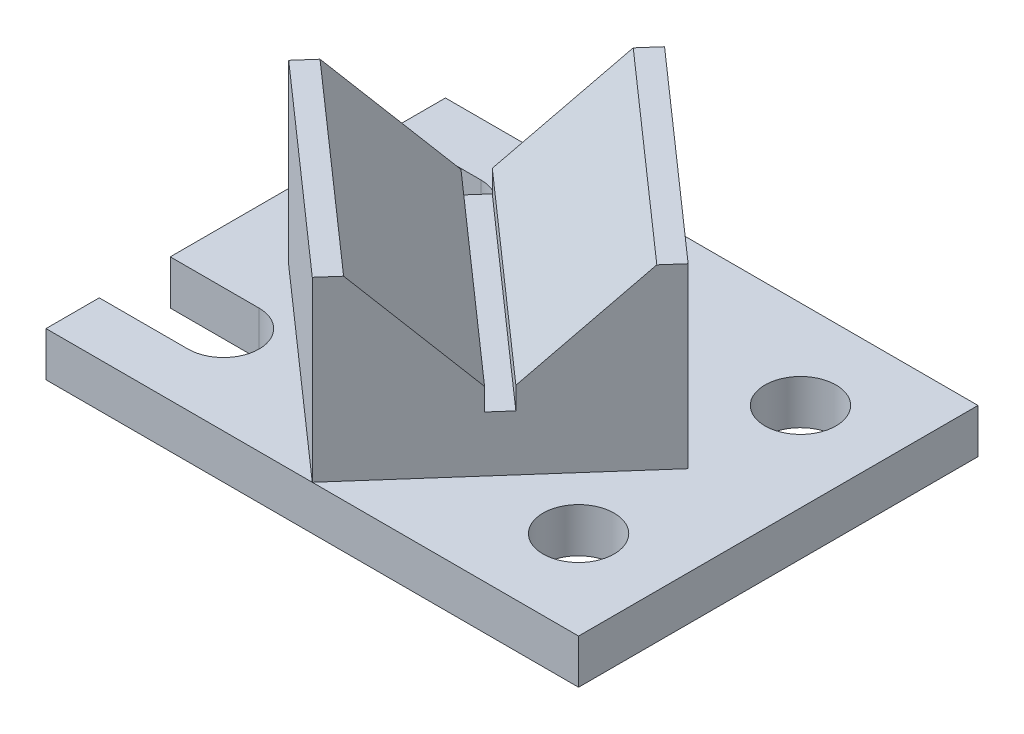
SolidWorks part; units mm, degrees
material "1060 Alloy"
ref_plane "Front Plane" through (0, 0, 0) normal (0, 0, 1) x (1, 0, 0)
ref_plane "Top Plane" through (0, 0, 0) normal (0, 1, 0) x (1, 0, 0)
ref_plane "Right Plane" through (0, 0, 0) normal (1, 0, 0) x (0, 0, -1)
sketch "Sketch3" plane through (0, 0, 0) normal (0, 1, 0) x (1, 0, 0)
  line L0 (0, 35.56) -> (25.4, 35.56)
  line L1 (0, 0) -> (152.4, 0)
  line L2 (0, 0) -> (0, 114.3)
  line L3 (0, 114.3) -> (152.4, 114.3)
  line L4 (152.4, 0) -> (152.4, 114.3)
  line L5 (25.4, 15.24) -> (0, 15.24)
  line L6 (-1000, 57.15) -> (49000, 57.15) construction
  line L7 (25.4, 99.06) -> (0, 99.06)
  line L8 (0, 78.74) -> (25.4, 78.74)
  circle A0 centre (127, 88.9) radius 10.16
  circle A1 centre (127, 25.4) radius 10.16
  arc A2 (25.4, 35.56) -> (25.4, 15.24) centre (25.4, 25.4) cw
  arc A3 (25.4, 78.74) -> (25.4, 99.06) centre (25.4, 88.9) ccw
  point P23 (0, 57.15)
  dimension "D6" = 20.32
  dimension "D1" = 114.3
  dimension "D2" = 152.4
  dimension "D3" = 25.4
  dimension "D4" = 25.4
  dimension "D5" = 25.4
  dimension "D7" = 25.4
  dimension "D8" = 20.32
  dimension "D9" = 25.4
extrude "Boss-Extrude2" add sketch "Sketch3" against normal blind 12.7 contours L6 L2 L0 A2 L5 L1 L4 A1 | L2 L6 L4 L3 L7 A3 L8 A0
sketch "Sketch4" plane through (0, 0, 0) normal (0, 1, 0) x (1, 0, 0)
  line L0 (76.2, 0) -> (19.05, 50.4016)
  line L1 (76.2, 0) -> (126.6016, 57.15)
  line L2 (19.05, 50.4016) -> (69.4516, 107.5516)
  line L3 (126.6016, 57.15) -> (69.4516, 107.5516)
  line L4 (0, 0) -> (152.4, 0) construction
  line L5 (-1000, 57.15) -> (49000, 57.15) construction
  line L6 (0, 35.56) -> (0, 78.74) construction
  point P12 (0, 57.15)
  dimension "D1" = 76.2
extrude "Boss-Extrude3" add sketch "Sketch4" along normal blind 50.8
sketch "Sketch5" plane through (42.8625, 0, 37.8012) normal (0.75, 0, 0.6614) x (0.6614, 0, -0.75)
  line L0 (50.4016, 50.8) -> (50.4016, 0) construction
  line L1 (50.4016, 50.8) -> (126.6016, 50.8) construction
  line L2 (56.7516, 50.8) -> (85.3266, 22.225)
  line L3 (85.3266, 22.225) -> (85.3266, 15.875)
  line L4 (85.3266, 15.875) -> (91.6766, 15.875)
  line L5 (88.5016, -949.2) -> (88.5016, 49050.8) construction
  line L6 (50.4016, 0) -> (100.8031, 0) construction
  line L7 (91.6766, 22.225) -> (91.6766, 15.875)
  line L8 (120.2516, 50.8) -> (91.6766, 22.225)
  line L9 (56.7516, 50.8) -> (120.2516, 50.8)
  point P11 (88.5016, 50.8)
  point P17 (88.5016, 15.875)
  dimension "D1" = 6.35
  dimension "D2" = 6.35
  dimension "D3" = 15.875
  dimension "D4" = 45
extrude "Cut-Extrude1" cut sketch "Sketch5" against normal through all both and the other way through all
